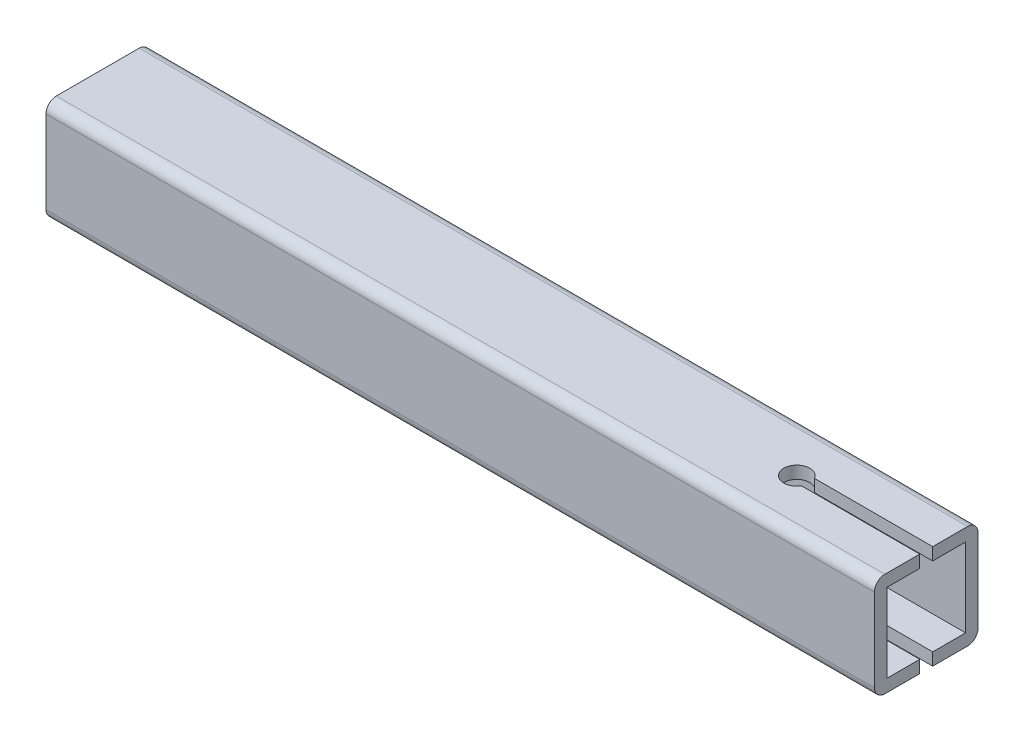
SolidWorks part; units mm, degrees
material "Plain Carbon Steel"
ref_plane "Front Plane" through (0, 0, 0) normal (0, 0, 1) x (1, 0, 0)
ref_plane "Top Plane" through (0, 0, 0) normal (0, 1, 0) x (1, 0, 0)
ref_plane "Right Plane" through (0, 0, 0) normal (1, 0, 0) x (0, 0, -1)
sketch "Sketch1" plane through (0, 0, 0) normal (1, 0, 0) x (0, 0, -1)
  line L0 (0, 2.54) -> (0, 22.86)
  line L1 (-2.54, 25.4) -> (-22.86, 25.4)
  line L2 (-25.4, 22.86) -> (-25.4, 2.54)
  line L3 (-22.86, 0) -> (-2.54, 0)
  line L4 (-3.048, 3.048) -> (-3.048, 22.352)
  line L5 (-3.048, 22.352) -> (-22.352, 22.352)
  line L6 (-22.352, 22.352) -> (-22.352, 3.048)
  line L7 (-22.352, 3.048) -> (-3.048, 3.048)
  arc A0 (-25.4, 2.54) -> (-22.86, 0) centre (-22.86, 2.54) ccw
  arc A1 (0, 2.54) -> (-2.54, 0) centre (-2.54, 2.54) cw
  arc A2 (0, 22.86) -> (-2.54, 25.4) centre (-2.54, 22.86) ccw
  arc A3 (-25.4, 22.86) -> (-22.86, 25.4) centre (-22.86, 22.86) cw
  arc A4 (-3.048, 22.352) -> (-3.048, 22.352) centre (-3.048, 22.352) ccw
  arc A5 (-22.352, 22.352) -> (-22.352, 22.352) centre (-22.352, 22.352) cw
  arc A6 (-22.352, 3.048) -> (-22.352, 3.048) centre (-22.352, 3.048) ccw
  arc A7 (-3.048, 3.048) -> (-3.048, 3.048) centre (-3.048, 3.048) cw
  point P12 (0, 0)
  point P15 (0, 25.4)
  point P18 (-25.4, 25.4)
  dimension "D3" = 2.54
  dimension "D1" = 25.4
  dimension "D2" = 25.4
  dimension "D4" = 3.048
extrude "Boss-Extrude1" add sketch "Sketch1" along normal blind 203.2
sketch "Sketch2" plane through (0, 25.4, 0) normal (0, 1, 0) x (1, 0, 0)
  line L0 (203.2, -2.54) -> (203.2, -22.86) construction
  line L1 (203.2, -11.1125) -> (174.1996, -11.1125)
  line L2 (203.2, -11.1125) -> (203.2, -14.2875)
  line L3 (203.2, -14.2875) -> (174.1996, -14.2875)
  line L5 (188.6998, -14.2875) -> (188.6998, -11.1125) construction
  line L6 (203.2, -12.7) -> (171.45, -12.7) construction
  arc A0 (174.1996, -11.1125) -> (174.1996, -14.2875) centre (171.45, -12.7) ccw
  point P152 (188.6998, -12.7)
  dimension "D3" = 6.35
  dimension "D1" = 3.175
  dimension "D2" = 31.75
extrude "Cut-Extrude1" cut sketch "Sketch2" against normal through all and the other way through all
